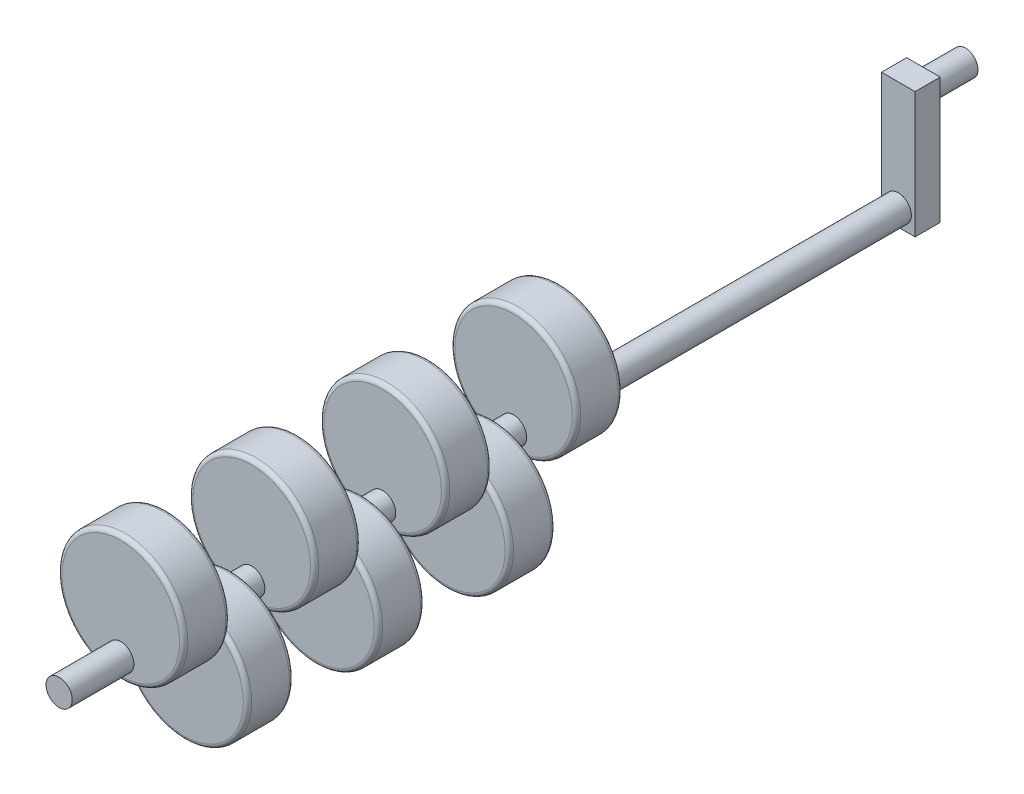
SolidWorks part; units mm, degrees
ref_plane "前视基准面" through (0, 0, 0) normal (0, 0, 1) x (1, 0, 0)
ref_plane "上视基准面" through (0, 0, 0) normal (0, 1, 0) x (1, 0, 0)
ref_plane "右视基准面" through (0, 0, 0) normal (1, 0, 0) x (0, 0, -1)
sketch "草图1" plane through (0, 0, 0) normal (0, 0, 1) x (1, 0, 0)
  circle A0 centre (0, 0) radius 1.5625
  dimension "D1" = 3.125
extrude "凸台-拉伸1" add sketch "草图1" along normal mid plane 90
sketch "草图2" plane through (0, 0, 45) normal (0, 0, 1) x (1, 0, 0)
  circle A0 centre (0, 5) radius 7.5
  dimension "D2" = 15
  dimension "D1" = 5
extrude "凸台-拉伸2" add sketch "草图2" against normal mid plane 5.5 from offset 10.1 offset against normal yes
pattern_linear "阵列(线性)1" count 4 spacing 15.6 along (0, 0, -1) of "凸台-拉伸2"
sketch "草图3" plane through (0, 0, 45) normal (0, 0, 1) x (1, 0, 0)
  circle A0 centre (0, -5) radius 7.5
  dimension "D2" = 15
  dimension "D1" = 5
extrude "凸台-拉伸3" add sketch "草图3" against normal mid plane 5.5 from offset 17.7 offset against normal yes
pattern_linear "阵列(线性)2" count 3 spacing 15.6 along (0, 0, -1) of "凸台-拉伸3"
fillet "圆角1" radius 0.5 14 edges at (7.5, 5, 37.65) (7.5, 5, 32.15) (7.5, -5, 30.05) (7.5, -5, 24.55) (7.5, -5, 14.45) (7.5, -5, 8.95) (7.5, 5, 22.05) (7.5, 5, 16.55) (7.5, 5, 6.45) (7.5, 5, 0.95) (7.5, -5, -1.15) (7.5, -5, -6.65) (7.5, 5, -9.15) (7.5, 5, -14.65)
sketch "草图4" plane through (0, 0, -45) normal (0, 0, -1) x (-1, 0, 0)
  circle A0 centre (0, 0) radius 1.5625
extrude "凸台-拉伸4" add sketch "草图4" along normal blind 10
sketch "草图5" plane through (0, 0, -55) normal (0, 0, -1) x (-1, 0, 0)
  line L1 (-2, -2) -> (2, -2)
  line L2 (-2, -2) -> (-2, 13)
  line L3 (-2, 13) -> (2, 13)
  line L4 (2, -2) -> (2, 13)
  point P4 (0, -2)
  dimension "D1" = 4
  dimension "D2" = 2
  dimension "D3" = 15
extrude "凸台-拉伸5" add sketch "草图5" along normal blind 3
sketch "草图6" plane through (0, 0, -58) normal (0, 0, -1) x (-1, 0, 0)
  line L0 (2, 13) -> (-2, 13) construction
  circle A0 centre (0, 11) radius 1.5
  point P2 (0, 0)
  point P4 (0, 0)
  dimension "D1" = 3
  dimension "D2" = 2
extrude "凸台-拉伸6" add sketch "草图6" along normal blind 5
